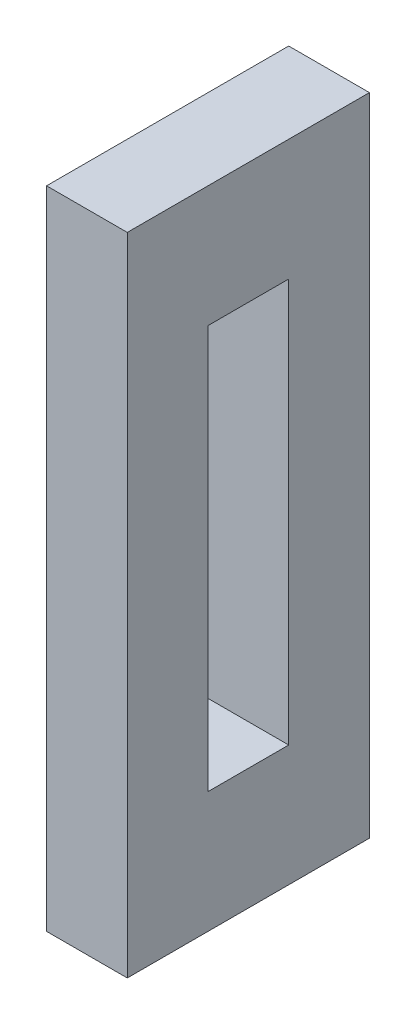
SolidWorks part; units mm, degrees
ref_plane "Front Plane" through (0, 0, 0) normal (0, 0, 1) x (1, 0, 0)
ref_plane "Top Plane" through (0, 0, 0) normal (0, 1, 0) x (1, 0, 0)
ref_plane "Right Plane" through (0, 0, 0) normal (1, 0, 0) x (0, 0, -1)
sketch "Sketch1" plane through (0, 0, 0) normal (1, 0, 0) x (0, -1, 0)
  line L1 (-40, -15) -> (40, -15)
  line L2 (-40, -15) -> (-40, 15)
  line L3 (-40, 15) -> (40, 15)
  line L4 (40, -15) -> (40, 15)
  line L5 (-40, -15) -> (40, 15) construction
  line L6 (-40, 15) -> (40, -15) construction
  line L7 (-25, 5) -> (25, 5)
  line L8 (-25, 5) -> (-25, -5)
  line L9 (-25, -5) -> (25, -5)
  line L10 (25, 5) -> (25, -5)
  line L11 (-25, 5) -> (25, -5) construction
  line L12 (-25, -5) -> (25, 5) construction
  point P0 (0, 0)
  point P5 (0, 0)
  dimension "D1" = 80
  dimension "D2" = 30
  dimension "D3" = 50
extrude "Boss-Extrude1" add sketch "Sketch1" along normal blind 10
